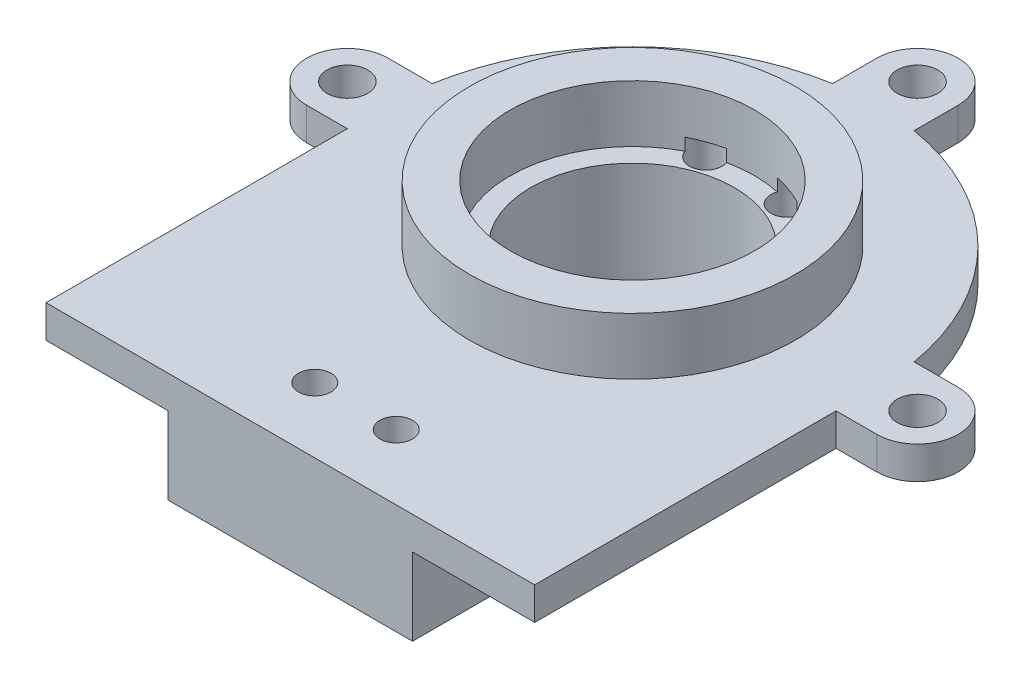
SolidWorks part; units mm, degrees
ref_plane "Спереди" through (0, 0, 0) normal (0, 0, 1) x (1, 0, 0)
ref_plane "Сверху" through (0, 0, 0) normal (0, 1, 0) x (1, 0, 0)
ref_plane "Справа" through (0, 0, 0) normal (1, 0, 0) x (0, 0, -1)
sketch "Эскиз1" plane through (0, 0, 0) normal (0, 1, 0) x (1, 0, 0)
  circle A0 centre (0, 0) radius 20
  circle A1 centre (0, 0) radius 15
  dimension "D1" = 40
  dimension "D2" = 30
extrude "Бобышка-Вытянуть1" add sketch "Эскиз1" along normal blind 7
sketch "Эскиз2" plane through (0, 0, 0) normal (0, -1, 0) x (1, 0, 0)
  circle A0 centre (0, 0) radius 70
  circle A1 centre (0, 0) radius 12.5
  dimension "D1" = 140
  dimension "D2" = 25
extrude "Бобышка-Вытянуть2" add sketch "Эскиз2" along normal blind 4
sketch "Эскиз3" plane through (0, -4, 0) normal (0, -1, 0) x (1, 0, 0)
  line L0 (10, -6.7) -> (10, 26.7) construction
  line L1 (15, -22) -> (-15, -22)
  line L2 (15, -22) -> (15, 42)
  line L3 (15, 42) -> (-15, 42)
  line L4 (-15, -22) -> (-15, 42)
  line L5 (-10, 26.7) -> (-10, -6.7) construction
  line L6 (-3.6083, -17) -> (3.6083, -17) construction
  line L7 (3.6083, 37) -> (-3.6083, 37) construction
  circle A0 centre (-5, 34) radius 2
  circle A1 centre (5, 34) radius 2
  circle A2 centre (-5, -14) radius 2
  circle A3 centre (5, -14) radius 2
  circle A4 centre (0, 0) radius 12.5
  dimension "D1" = 5
  dimension "D2" = 5
  dimension "D3" = 5
  dimension "D4" = 5
extrude "Бобышка-Вытянуть3" add sketch "Эскиз3" along normal blind 9.5
sketch "Эскиз4" plane through (0, 0, 0) normal (0, 1, 0) x (1, 0, 0)
  line L0 (-1000, 0) -> (49000, 0) construction
  line L1 (-30, 0) -> (-30, -42)
  line L2 (-30, -42) -> (30, -42)
  line L3 (30, -42) -> (30, 0)
  arc A0 (30, 0) -> (-30, 0) centre (0, 0) ccw
  circle A1 centre (0, 0) radius 81.1685
  dimension "D1" = 60
  dimension "D2" = 60
  dimension "D3" = 42
extrude "Вырез-Вытянуть1" cut sketch "Эскиз4" against normal blind 9.5
sketch "Эскиз6" plane through (0, -13.5, 0) normal (0, -1, 0) x (1, 0, 0)
  circle A0 centre (-5, 34) radius 2
  circle A1 centre (5, 34) radius 2
  circle A2 centre (-5, -14) radius 2
  circle A3 centre (5, -14) radius 2
extrude "Вырез-Вытянуть2" cut sketch "Эскиз6" against normal blind 15
sketch "Эскиз7" plane through (0, 0, 0) normal (0, 1, 0) x (1, 0, 0)
  line L0 (-1000, 0) -> (49000, 0) construction
  line L1 (0, -1000) -> (0, 49000) construction
  line L2 (-35, 5) -> (-27, 5)
  line L3 (-27, 5) -> (-27, -5)
  line L4 (-27, -5) -> (-35, -5)
  line L5 (-5, 35) -> (-5, 27)
  line L6 (-5, 27) -> (5, 27)
  line L7 (5, 27) -> (5, 35)
  line L8 (35, 5) -> (27, 5)
  line L9 (27, 5) -> (27, -5)
  line L10 (27, -5) -> (35, -5)
  circle A0 centre (-35, 0) radius 2.5
  circle A1 centre (35, 0) radius 2.5
  circle A2 centre (0, 35) radius 2.5
  arc A3 (-35, 5) -> (-35, -5) centre (-35, 0) ccw
  arc A5 (5, 35) -> (-5, 35) centre (0, 35) ccw
  arc A6 (35, -5) -> (35, 5) centre (35, 0) ccw
  dimension "D1" = 5
  dimension "D3" = 5
  dimension "D5" = 5
  dimension "D7" = 10
  dimension "D8" = 10
  dimension "D2" = 35
  dimension "D4" = 70
  dimension "D6" = 35
  dimension "D9" = 8
  dimension "D10" = 8
  dimension "D11" = 8
  dimension "D12" = 10
  dimension "D13" = 10
  dimension "D14" = 8
extrude "Бобышка-Вытянуть4" add sketch "Эскиз7" against normal blind 4
